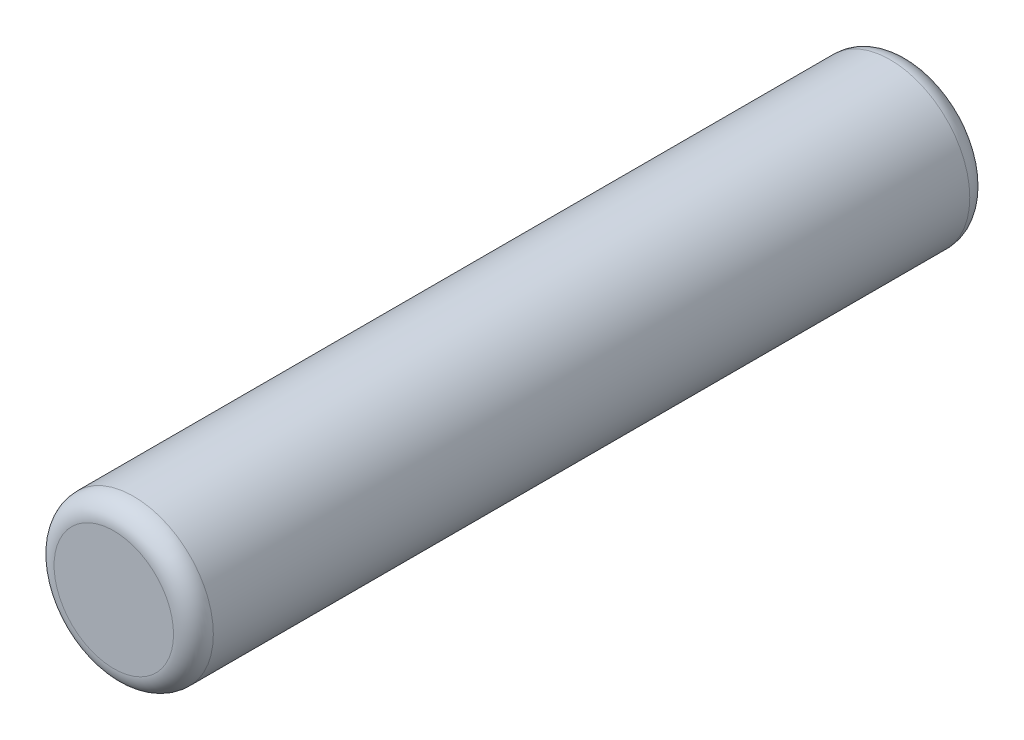
SolidWorks part; units mm, degrees
ref_plane "Front Plane" through (0, 0, 0) normal (0, 0, 1) x (1, 0, 0)
ref_plane "Top Plane" through (0, 0, 0) normal (0, 1, 0) x (1, 0, 0)
ref_plane "Right Plane" through (0, 0, 0) normal (1, 0, 0) x (0, 0, -1)
sketch "Sketch2" plane through (0, 0, 0) normal (0, 0, 1) x (1, 0, 0)
  circle A0 centre (0, 0) radius 4
  dimension "D1" = 8
extrude "Boss-Extrude1" add sketch "Sketch2" along normal mid plane 40
fillet "Fillet1" radius 1 2 edges at (4, 0, -20) (4, 0, 20)
